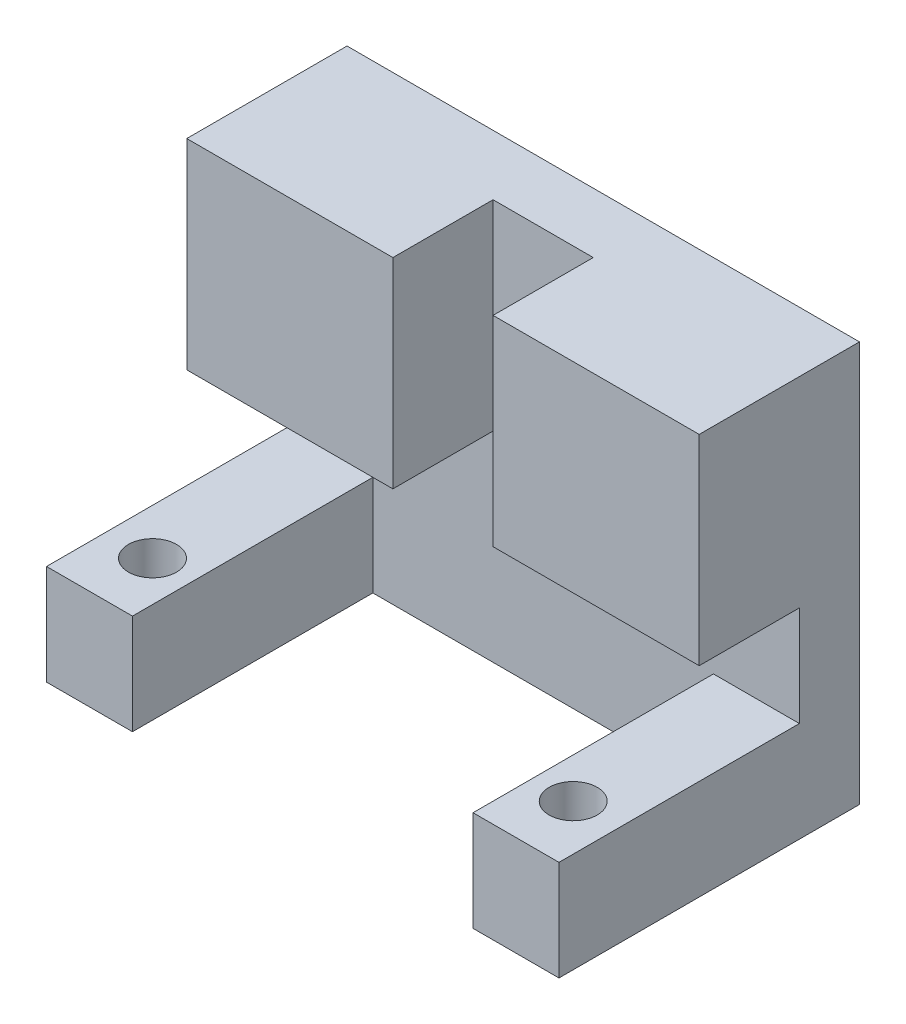
SolidWorks part; units mm, degrees
ref_plane "正面" through (0, 0, 0) normal (0, 0, 1) x (1, 0, 0)
ref_plane "平面" through (0, 0, 0) normal (0, 1, 0) x (1, 0, 0)
ref_plane "右側面" through (0, 0, 0) normal (1, 0, 0) x (0, 0, -1)
sketch "ｽｹｯﾁ1" plane through (0, 0, 0) normal (0, 0, 1) x (1, 0, 0)
  line L1 (-12.79, 10) -> (12.79, 10)
  line L2 (-12.79, 10) -> (-12.79, -10)
  line L3 (-12.79, -10) -> (12.79, -10)
  line L4 (12.79, 10) -> (12.79, -10)
  line L5 (-12.79, 10) -> (12.79, -10) construction
  line L6 (-12.79, -10) -> (12.79, 10) construction
  point P0 (0, 0)
  dimension "D1" = 20
  dimension "D2" = 25.58
extrude "ﾎﾞｽ - 押し出し1" add sketch "ｽｹｯﾁ1" along normal blind 15
sketch "ｽｹｯﾁ4" plane through (0, 0, 15) normal (0, 0, 1) x (1, 0, 0)
  line L0 (-12.79, 10) -> (-12.79, -10) construction
  line L1 (12.79, 10) -> (-12.79, 10)
  line L2 (12.79, 10) -> (12.79, -5)
  line L3 (12.79, -5) -> (-12.79, -5)
  line L4 (-12.79, 10) -> (-12.79, -5)
  line L5 (-12.79, -10) -> (12.79, -10) construction
  dimension "D1" = 5
extrude "ｶｯﾄ - 押し出し3" cut sketch "ｽｹｯﾁ4" against normal blind 7
sketch "ｽｹｯﾁ5" plane through (12.79, 0, 0) normal (1, 0, 0) x (0, 0, -1)
  line L1 (-8, -5) -> (-3, -5)
  line L2 (-8, -5) -> (-8, 0)
  line L3 (-8, 0) -> (-3, 0)
  line L4 (-3, -5) -> (-3, 0)
  dimension "D1" = 12
  dimension "D2" = 5
extrude "ｶｯﾄ - 押し出し4" cut sketch "ｽｹｯﾁ5" against normal through all
sketch "ｽｹｯﾁ6" plane through (0, 10, 0) normal (0, 1, 0) x (1, 0, 0)
  line L0 (12.79, -8) -> (-12.79, -8) construction
  line L1 (-2.5, -8) -> (2.5, -8)
  line L2 (-2.5, -8) -> (-2.5, -3)
  line L3 (-2.5, -3) -> (2.5, -3)
  line L4 (2.5, -8) -> (2.5, -3)
  point P6 (0, -3)
  dimension "D1" = 5
  dimension "D2" = 5
extrude "ｶｯﾄ - 押し出し5" cut sketch "ｽｹｯﾁ6" against normal up to next
hole_wizard "M2 すきま穴1" positions "ｽｹｯﾁ7" profile "ｽｹｯﾁ8" hole size "M2" standard "JIS" end condition through all
sketch "ｽｹｯﾁ7" plane through (0, -5, 0) normal (0, 1, 0) x (1, 0, 0)
  line L0 (-10.5, -12) -> (10.5, -12)
  line L2 (-12.79, -15) -> (12.79, -15) construction
  point P0 (10.5, -12)
  point P2 (-10.5, -12)
  point P12 (0, -15)
  point P13 (0, -12)
  dimension "D1" = 21
  dimension "D2" = 3
sketch "ｽｹｯﾁ8" plane through (10.5, -5, 12) normal (1, 0, 0) x (0, 0, 1)
  line L0 (0, 0) -> (0, 5)
  line L1 (0, 5) -> (1.2, 5)
  line L2 (1.2, 5) -> (1.2, 0)
  line L5 (1.2, 0) -> (0, 0)
  line L11 (0, -6.35) -> (0, 107.95) construction
  dimension "通し穴の直径" = 2.4
  dimension "通し穴の深さ" = 5
sketch "ｽｹｯﾁ10" plane through (0, -5, 0) normal (0, 1, 0) x (1, 0, 0)
  line L0 (-12.79, -3) -> (12.79, -3) construction
  line L1 (8.5, -3) -> (-8.5, -3)
  line L2 (8.5, -3) -> (8.5, -15)
  line L3 (8.5, -15) -> (-8.5, -15)
  line L4 (-8.5, -3) -> (-8.5, -15)
  line L5 (-12.79, -15) -> (12.79, -15) construction
  point P8 (0, -15)
  point P9 (0, -15)
  dimension "D1" = 17
extrude "ｶｯﾄ - 押し出し7" cut sketch "ｽｹｯﾁ10" against normal through all
